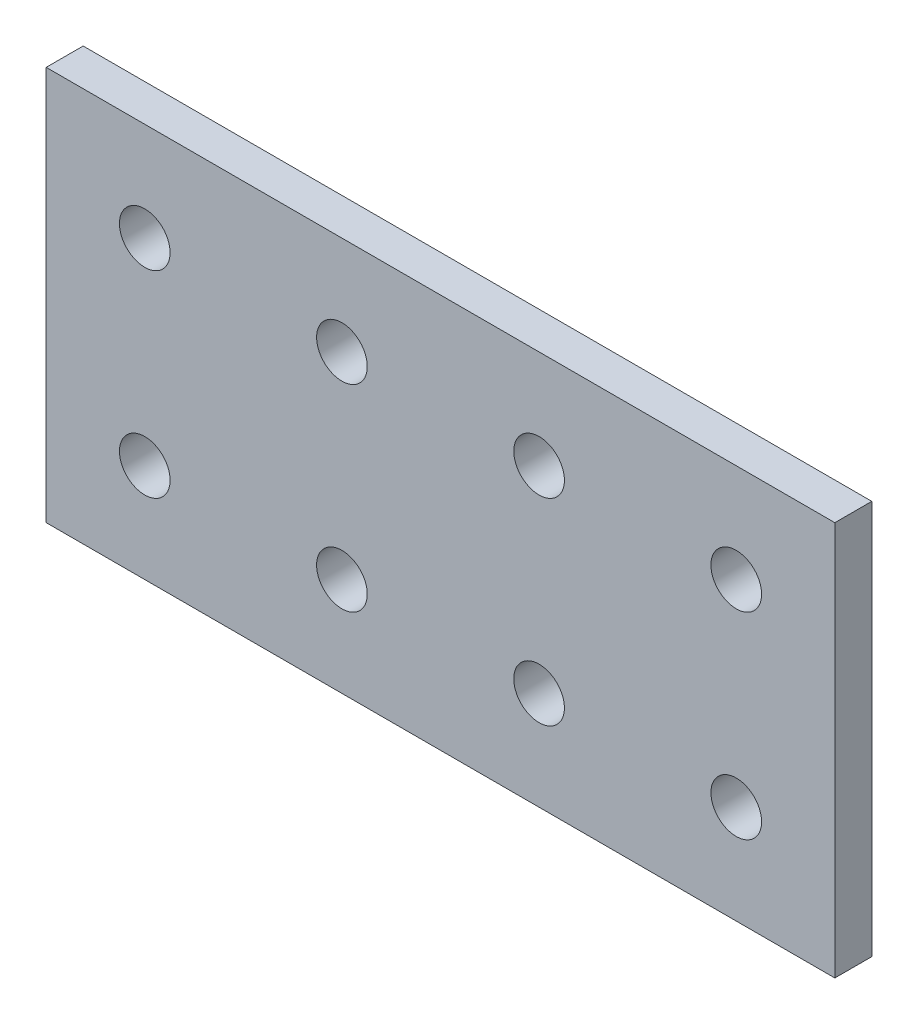
SolidWorks part; units mm, degrees
ref_plane "Front Plane" through (0, 0, 0) normal (0, 0, 1) x (1, 0, 0)
ref_plane "Top Plane" through (0, 0, 0) normal (0, 1, 0) x (1, 0, 0)
ref_plane "Right Plane" through (0, 0, 0) normal (1, 0, 0) x (0, 0, -1)
sketch "Sketch1" plane through (0, 0, 0) normal (0, 0, 1) x (1, 0, 0)
  line L0 (0, 0) -> (0, 50.8)
  line L1 (12.7, 12.7) -> (38.1, 12.7) construction
  line L2 (38.1, 12.7) -> (63.5, 12.7) construction
  line L3 (63.5, 12.7) -> (88.9, 12.7) construction
  line L4 (101.6, 50.8) -> (0, 50.8)
  line L5 (101.6, 0) -> (0, 0)
  line L6 (12.7, 12.7) -> (12.7, 38.1) construction
  line L7 (101.6, 50.8) -> (101.6, 0)
  line L8 (12.7, 38.1) -> (38.1, 38.1) construction
  line L9 (38.1, 38.1) -> (63.5, 38.1) construction
  line L10 (63.5, 38.1) -> (88.9, 38.1) construction
  line L11 (38.1, 12.7) -> (38.1, 38.1) construction
  line L12 (63.5, 12.7) -> (63.5, 38.1) construction
  line L13 (88.9, 12.7) -> (88.9, 38.1) construction
  circle A0 centre (12.7, 12.7) radius 3.2639
  circle A1 centre (38.1, 12.7) radius 3.2639
  circle A2 centre (63.5, 12.7) radius 3.2639
  circle A3 centre (88.9, 12.7) radius 3.2639
  circle A4 centre (12.7, 38.1) radius 3.2639
  circle A5 centre (38.1, 38.1) radius 3.2639
  circle A6 centre (63.5, 38.1) radius 3.2639
  circle A7 centre (88.9, 38.1) radius 3.2639
  dimension "D1" = 25.4
  dimension "E" = 6.5278
  dimension "D2" = 12.7
  dimension "C" = 50.8
  dimension "D3" = 12.7
  dimension "B" = 101.6
extrude "Boss-Extrude1" add sketch "Sketch1" along normal mid plane 4.7625
